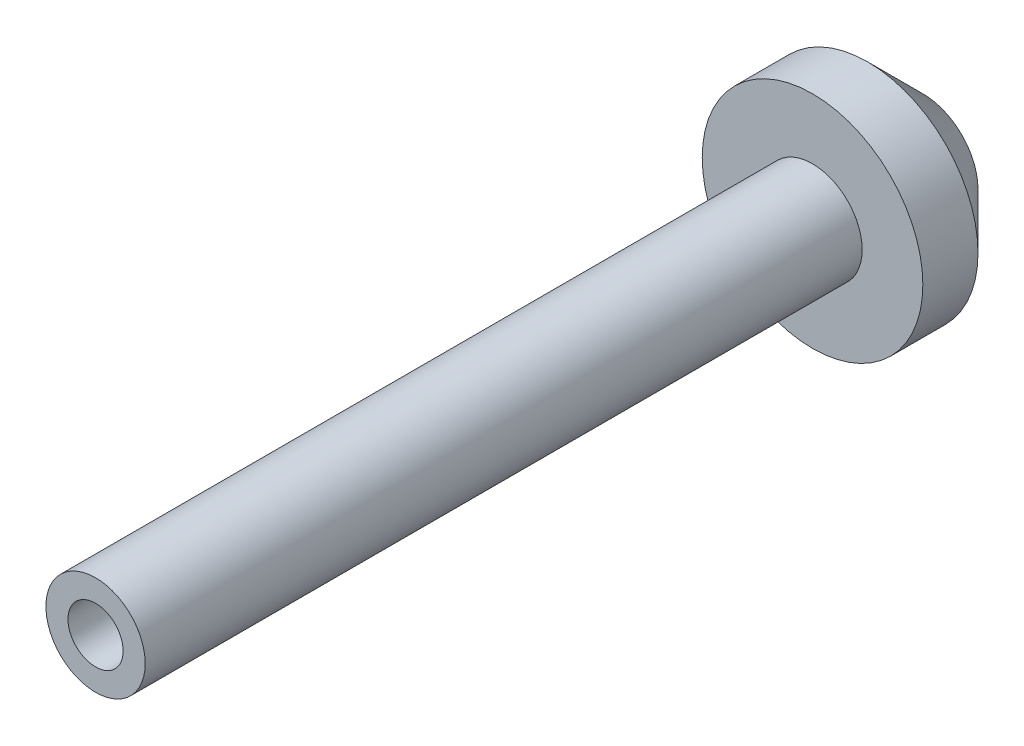
SolidWorks part; units mm, degrees
ref_plane "Front Plane" through (0, 0, 0) normal (0, 0, 1) x (1, 0, 0)
ref_plane "Top Plane" through (0, 0, 0) normal (0, 1, 0) x (1, 0, 0)
ref_plane "Right Plane" through (0, 0, 0) normal (1, 0, 0) x (0, 0, -1)
sketch "Sketch1" plane through (0, 0, 0) normal (0, 0, 1) x (1, 0, 0)
  circle A0 centre (0, 0) radius 5
  dimension "D1" = 10
extrude "Boss-Extrude1" add sketch "Sketch1" along normal blind 5
sketch "Sketch2" plane through (0, 0, 5) normal (0, 0, 1) x (1, 0, 0)
  circle A0 centre (0, 0) radius 2.25
  dimension "D1" = 4.5
extrude "Boss-Extrude2" add sketch "Sketch2" along normal blind 32.5
sketch "Sketch3" plane through (0, 0, 37.5) normal (0, 0, 1) x (1, 0, 0)
  circle A0 centre (0, 0) radius 1.25
  dimension "D1" = 2.5
extrude "Cut-Extrude1" cut sketch "Sketch3" against normal blind 10
chamfer "Chamfer1" distance 2.5 angle 45 1 edges at (5, 0, 0)
